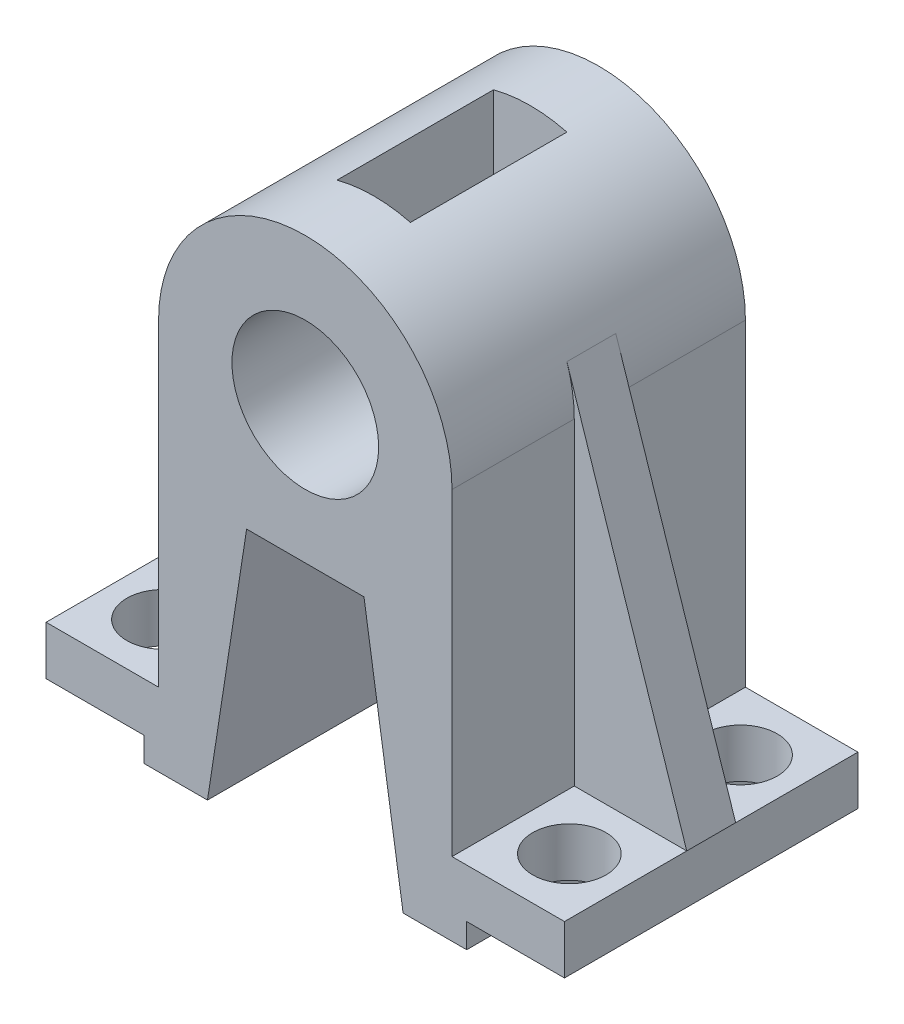
SolidWorks part; units mm, degrees
ref_plane "Front Plane" through (0, 0, 0) normal (0, 0, 1) x (1, 0, 0)
ref_plane "Top Plane" through (0, 0, 0) normal (0, 1, 0) x (1, 0, 0)
ref_plane "Right Plane" through (0, 0, 0) normal (1, 0, 0) x (0, 0, -1)
sketch "Sketch1" plane through (0, 0, 0) normal (0, 0, 1) x (1, 0, 0)
  line L0 (0, 0) -> (0, 52) construction
  line L1 (-12, 52) -> (12, 52)
  line L2 (12, 52) -> (20, 0)
  line L3 (20, 0) -> (33, 0)
  line L4 (33, 0) -> (33, 5)
  line L5 (33, 5) -> (53, 5)
  line L6 (53, 5) -> (53, 15)
  line L7 (53, 15) -> (30, 15)
  line L8 (30, 15) -> (30, 80)
  line L11 (-30, 15) -> (-30, 80)
  line L12 (-53, 15) -> (-30, 15)
  line L13 (-53, 5) -> (-53, 15)
  line L14 (-33, 5) -> (-53, 5)
  line L15 (-33, 0) -> (-33, 5)
  line L16 (-20, 0) -> (-33, 0)
  line L17 (-12, 52) -> (-20, 0)
  arc A0 (30, 80) -> (-30, 80) centre (0, 80) ccw
  circle A1 centre (0, 80) radius 15
  dimension "D9" = 30
  dimension "D1" = 24
  dimension "D2" = 40
  dimension "D3" = 66
  dimension "D4" = 10
  dimension "D5" = 15
  dimension "D6" = 52
  dimension "D7" = 60
  dimension "D8" = 106
  dimension "D10" = 80
extrude "Boss-Extrude1" add sketch "Sketch1" along normal blind 60
sketch "Sketch2" plane through (0, 15, 0) normal (0, 1, 0) x (1, 0, 0)
  line L0 (-41.5, -12.5) -> (-41.5, -47.5) construction
  line L1 (-53, -30) -> (-38.3823, -30) construction
  line L2 (-53, -60) -> (-53, 0) construction
  line L3 (-30, 0) -> (-53, 0) construction
  line L4 (0, 0) -> (0, -32.822) construction
  line L5 (53, -30) -> (38.3823, -30) construction
  line L6 (41.5, -12.5) -> (41.5, -47.5) construction
  circle A0 centre (-41.5, -12.5) radius 7.5
  circle A1 centre (-41.5, -47.5) radius 7.5
  circle A2 centre (41.5, -47.5) radius 7.5
  circle A3 centre (41.5, -12.5) radius 7.5
  point P8 (-41.5, -30)
  point P12 (-41.5, 0)
  dimension "D2" = 15
  dimension "D1" = 35
extrude "Cut-Extrude1" cut sketch "Sketch2" against normal through all
ref_plane "Plane1" through (0, 80, 0) normal (0, 1, 0) x (1, 0, 0)
sketch "Sketch3" plane through (0, 80, 0) normal (0, 1, 0) x (1, 0, 0)
  line L0 (53, -60) -> (53, 0) construction
  line L1 (-7.5, -14) -> (7.5, -14)
  line L2 (-7.5, -14) -> (-7.5, -46)
  line L3 (-7.5, -46) -> (7.5, -46)
  line L4 (7.5, -14) -> (7.5, -46)
  point P4 (0, -14)
  point P8 (53, -30)
  point P9 (7.5, -30)
  dimension "D1" = 15
  dimension "D2" = 32
extrude "Cut-Extrude2" cut sketch "Sketch3" along normal through all
ref_plane "Plane2" through (0, 0, 30) normal (0, 0, 1) x (1, 0, 0)
sketch "Sketch4" plane through (0, 0, 30) normal (0, 0, 1) x (1, 0, 0)
  line L0 (28.4936, 89.3871) -> (53, 15)
  arc A0 (30, 80) -> (-30, 80) centre (0, 80) ccw construction
rib "Rib3" sketch "Sketch4" sketch "Sketch4" thickness 10 extrusion direction parallel to sketch draft on no parameters "D1"=10
mirror "Mirror1" about plane through (0, 0, 0) normal (1, 0, 0) of "Rib3"
